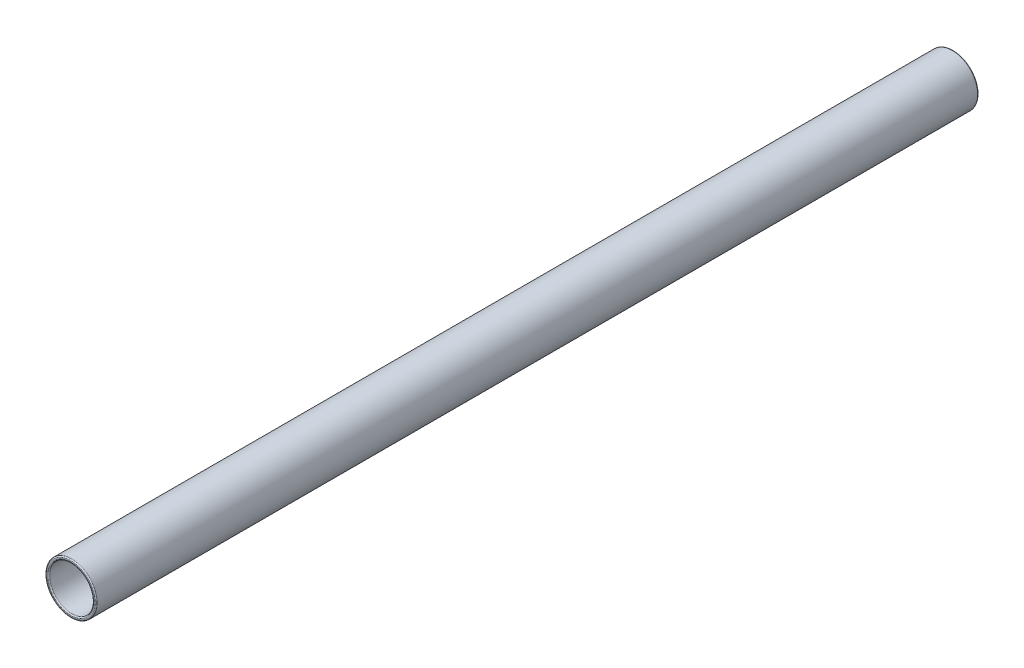
SolidWorks part; units mm, degrees
ref_plane "Front Plane" through (0, 0, 0) normal (0, 0, 1) x (1, 0, 0)
ref_plane "Top Plane" through (0, 0, 0) normal (0, 1, 0) x (1, 0, 0)
ref_plane "Right Plane" through (0, 0, 0) normal (1, 0, 0) x (0, 0, -1)
sketch "Sketch1" plane through (0, 0, 0) normal (0, 0, 1) x (1, 0, 0)
  circle A0 centre (0, 0) radius 11.5
  dimension "D1" = 23
extrude "Extrude-Thin1" add sketch "Sketch1" along normal mid plane 400 thin thin type one direction reverse wall 1.5
fillet "Fillet1" radius 0.5 4 edges at (10, 0, -200) (11.5, 0, -200) (10, 0, 200) (11.5, 0, 200)
